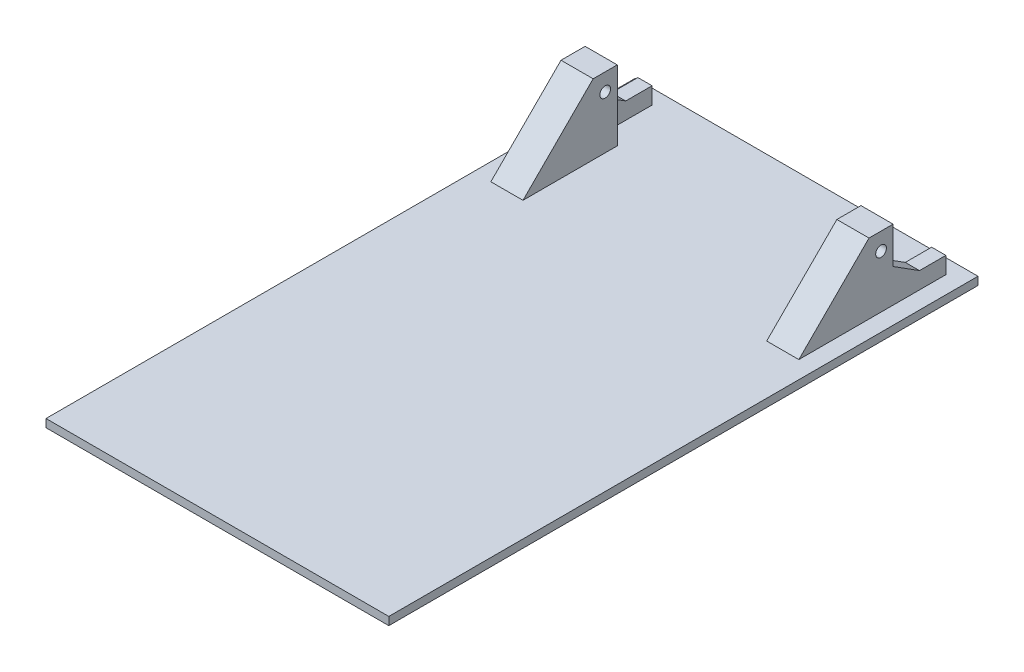
SolidWorks part; units mm, degrees
ref_plane "Front Plane" through (0, 0, 0) normal (0, 0, 1) x (1, 0, 0)
ref_plane "Top Plane" through (0, 0, 0) normal (0, 1, 0) x (1, 0, 0)
ref_plane "Right Plane" through (0, 0, 0) normal (1, 0, 0) x (0, 0, -1)
sketch "Sketch1" plane through (0, 0, 0) normal (0, 1, 0) x (1, 0, 0)
  line L1 (-32, 55) -> (32, 55)
  line L2 (-32, 55) -> (-32, -55)
  line L3 (-32, -55) -> (32, -55)
  line L4 (32, 55) -> (32, -55)
  line L5 (-32, 55) -> (32, -55) construction
  line L6 (-32, -55) -> (32, 55) construction
  point P0 (0, 0)
  dimension "D1" = 64
  dimension "D2" = 110
extrude "Boss-Extrude1" add sketch "Sketch1" along normal blind 1.5
sketch "Sketch2" plane through (0, 1.5, 0) normal (0, 1, 0) x (1, 0, 0)
  line L1 (32, 55) -> (-32, 55) construction
  line L2 (-32, 55) -> (-32, -55) construction
  line L3 (-28.75, 42.4) -> (-22.75, 42.4)
  line L4 (-28.75, 42.4) -> (-28.75, 37.9)
  line L5 (-28.75, 37.9) -> (-22.75, 37.9)
  line L6 (-22.75, 37.9) -> (-22.75, 42.4)
  dimension "D1" = 6
  dimension "D2" = 3.25
  dimension "D3" = 4.5
  dimension "D4" = 12.6
extrude "Boss-Extrude2" add sketch "Sketch2" along normal blind 13.1
sketch "Sketch3" plane through (-28.75, 0, 0) normal (-1, 0, 0) x (0, 0, 1)
  line L0 (-42.4, 7.75) -> (-47.325, 4.625)
  line L1 (-55, 1.5) -> (55, 1.5) construction
  line L2 (-52.25, 1.5) -> (-42.4, 1.5)
  line L3 (-42.4, 1.5) -> (-42.4, 7.75)
  line L4 (-37.9, 14.6) -> (-24.8, 1.5)
  line L5 (-37.9, 14.6) -> (-37.9, 1.5)
  line L6 (-37.9, 1.5) -> (-24.8, 1.5)
  line L7 (-42.4, 14.6) -> (-42.4, 1.5) construction
  line L8 (-47.325, 4.625) -> (-52.25, 4.625)
  line L9 (-52.25, 4.625) -> (-52.25, 1.5)
  dimension "D1" = 6.25
  dimension "D2" = 13.1
  dimension "D3" = 9.85
extrude "Boss-Extrude3" add sketch "Sketch3" against normal blind 2.65
sketch "Sketch6" plane through (-26.1, 0, 0) normal (1, 0, 0) x (0, 0, -1)
  line L0 (24.8, 1.5) -> (37.9, 1.5)
  line L1 (37.9, 1.5) -> (37.9, 14.6)
  line L2 (37.9, 14.6) -> (24.8, 1.5)
extrude "Boss-Extrude4" add sketch "Sketch6" along normal up to surface (3.35 mm away) up to face at (-22.75, 8.05, -40.15)
sketch "Sketch7" plane through (-28.75, 0, 0) normal (-1, 0, 0) x (0, 0, 1)
  line L0 (-42.4, 14.6) -> (-37.9, 14.6) construction
  circle A0 centre (-40.15, 11.35) radius 1
  point P5 (-40.15, 14.6)
  dimension "D2" = 2
  dimension "D1" = 3.25
extrude "Cut-Extrude1" cut sketch "Sketch7" against normal up to surface (6 mm away) up to face at (-22.75, 8.05, -36.875)
mirror "Mirror1" about plane through (0, 0, 0) normal (1, 0, 0) of "Boss-Extrude4", "Boss-Extrude2", "Boss-Extrude3", "Cut-Extrude1"
